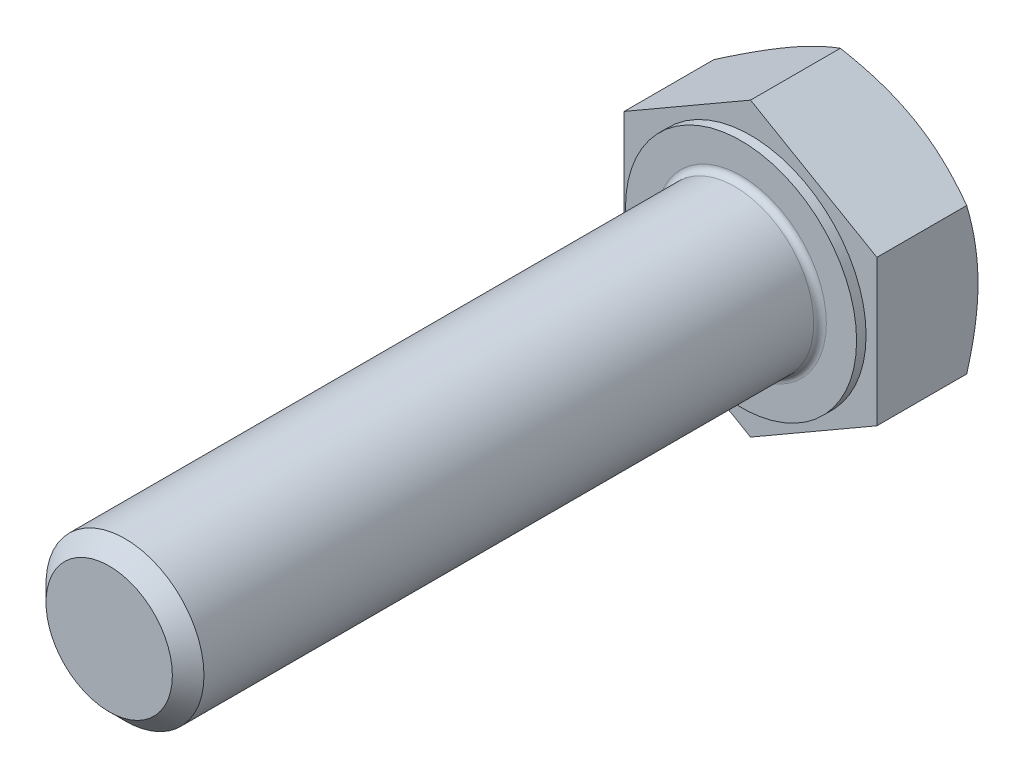
SolidWorks part; units mm, degrees
ref_plane "Přední rovina" through (0, 0, 0) normal (0, 0, 1) x (1, 0, 0)
ref_plane "Vrchní rovina" through (0, 0, 0) normal (0, 1, 0) x (1, 0, 0)
ref_plane "Pravá rovina" through (0, 0, 0) normal (1, 0, 0) x (0, 0, -1)
sketch "Skica1" plane through (0, 0, 0) normal (0, 0, 1) x (1, 0, 0)
  line L1 (8, -4.6188) -> (8, 4.6188)
  line L2 (8, 4.6188) -> (0, 9.2376)
  line L3 (0, 9.2376) -> (-8, 4.6188)
  line L4 (-8, 4.6188) -> (-8, -4.6188)
  line L5 (-8, -4.6188) -> (0, -9.2376)
  line L6 (0, -9.2376) -> (8, -4.6188)
  circle A0 centre (0, 0) radius 8 construction
  dimension "s" = 16
extrude "Vysunout1" add sketch "Skica1" along normal blind 6.4
sketch "Skica2" plane through (0, 0, 0) normal (0, 1, 0) x (1, 0, 0)
  line L0 (8, 0) -> (19.0851, 0)
  line L1 (19.0851, 0) -> (19.0851, -6.4)
  line L2 (19.0851, -6.4) -> (8, 0)
  line L3 (8, -6.4) -> (0, -6.4) construction
  line L4 (0, 0) -> (0, -6.4) construction
  dimension "D1" = 30
revolve "Odebrat otočením1" cut sketch "Skica2" angle 360 about L4
sketch "Skica3" plane through (0, 0, 6.4) normal (0, 0, 1) x (1, 0, 0)
  circle A0 centre (0, 0) radius 7.315
  dimension "dw" = 14.63
extrude "Vysunout2" add sketch "Skica3" along normal blind 0.6
sketch "Skica4" plane through (0, 0, 7) normal (0, 0, 1) x (1, 0, 0)
  circle A0 centre (0, 0) radius 5
  dimension "M" = 10
extrude "Vysunout3" add sketch "Skica4" along normal blind 40
cosmetic thread "Kosmetický závit1" parameters "D2"=8.5
chamfer "Zkosit1" distance 1 angle 45 1 edges at (5, 0, 47)
fillet "Zaoblit1" radius 0.4 1 edges at (5, 0, 7)
equation "\"D1@Zkosit1\" = \"M@Skica4\" * 0.1"
equation "\"D2@Kosmetický závit1\" = 0.85 * \"M@Skica4\""
